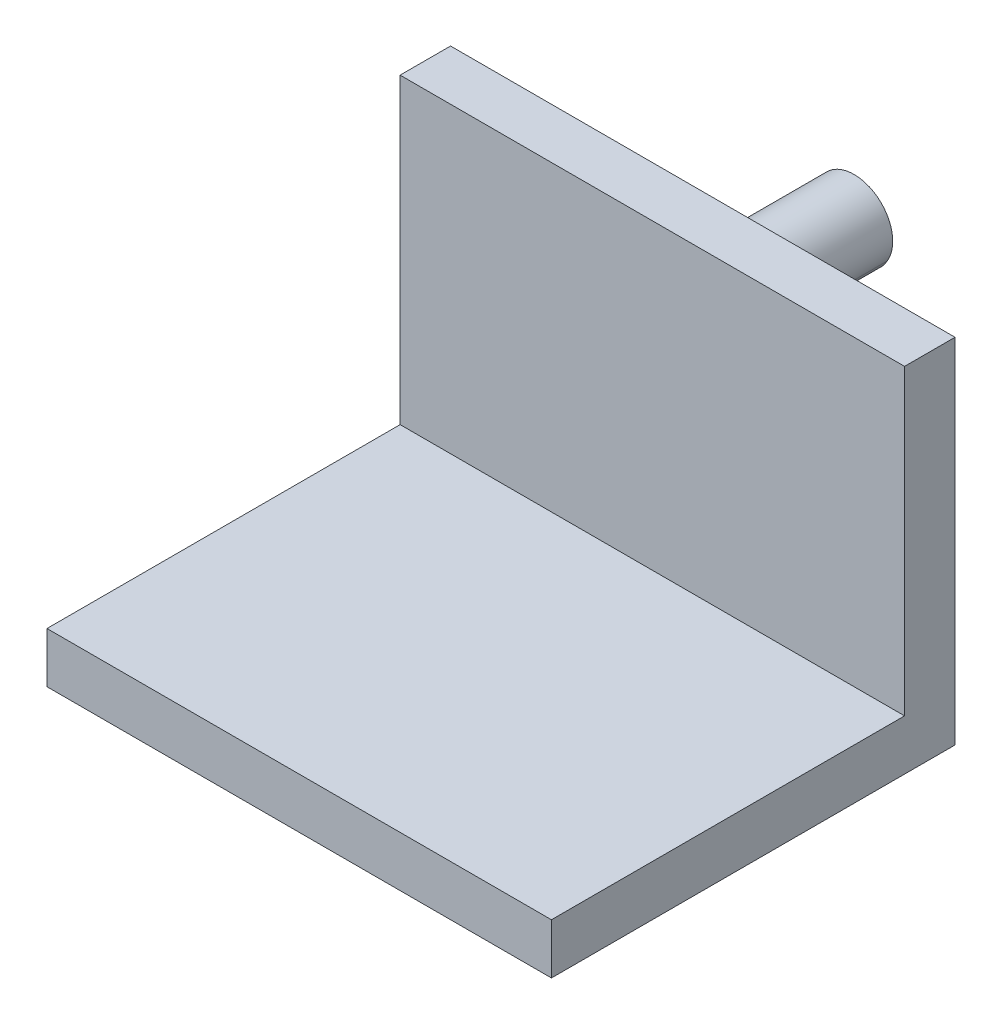
SolidWorks part; units mm, degrees
ref_plane "Front Plane" through (0, 0, 0) normal (0, 0, 1) x (1, 0, 0)
ref_plane "Top Plane" through (0, 0, 0) normal (0, 1, 0) x (1, 0, 0)
ref_plane "Right Plane" through (0, 0, 0) normal (1, 0, 0) x (0, 0, -1)
sketch "Sketch1" plane through (0, 0, 0) normal (0, 0, 1) x (1, 0, 0)
  line L0 (-66.057, 0) -> (58.5523, 0) construction
  line L1 (0, 49.7601) -> (0, -50.0946) construction
  line L3 (50, 35) -> (-50, 35)
  line L4 (50, 35) -> (50, -35)
  line L5 (50, -35) -> (-50, -35)
  line L6 (-50, 35) -> (-50, -35)
  dimension "D1" = 100
  dimension "D2" = 70
extrude "Boss-Extrude1" add sketch "Sketch1" along normal blind 10
sketch "Sketch2" plane through (-50, 0, 0) normal (-1, 0, 0) x (0, 0, 1)
  line L0 (10, -25) -> (80, -25)
  line L1 (10, 35) -> (10, -35) construction
  line L2 (80, -25) -> (80, -35)
  line L3 (80, -35) -> (10, -35)
  line L4 (10, -35) -> (10, -25)
  dimension "D1" = 70
  dimension "D2" = 10
extrude "Boss-Extrude3" add sketch "Sketch2" against normal blind 100
sketch "Sketch3" plane through (0, 0, 0) normal (0, 0, -1) x (-1, 0, 0)
  line L0 (0, 15) -> (-20.5318, 15) construction
  line L1 (0, 15) -> (0, 30.1359) construction
  line L2 (-50, 35) -> (-50, -35) construction
  line L3 (-50, -35) -> (50, -35) construction
  circle A0 centre (0, 15) radius 7.5
  dimension "D3" = 15
  dimension "D1" = 50
  dimension "D2" = 50
extrude "Boss-Extrude4" add sketch "Sketch3" along normal blind 30
sketch "Sketch4" plane through (0, 0, 0) normal (0, 0, -1) x (-1, 0, 0)
  line L0 (0, 15.3) -> (-20.8817, 15.3) construction
  line L1 (0, 15.3) -> (0, 30.8123) construction
  line L5 (-50, -35) -> (50, -35) construction
  line L6 (-50, 35) -> (-50, -35) construction
  circle A1 centre (0, 15.3) radius 7.65
  dimension "D1" = 15.3
  dimension "D2" = 50.3
  dimension "D3" = 50
extrude "Boss-Extrude5" add sketch "Sketch4" along normal blind 30
sketch "Sketch5" plane through (0, 0, 0) normal (0, 0, -1) x (-1, 0, 0)
  line L0 (0.3, 15) -> (-19.092, 15) construction
  line L1 (0.3, 15) -> (0.3, 33.1988) construction
  line L2 (-50, -35) -> (50, -35) construction
  line L3 (-50, 35) -> (-50, -35) construction
  circle A0 centre (0.3, 15) radius 7.65
  dimension "D3" = 15.3
  dimension "D1" = 50
  dimension "D2" = 50.3
extrude "Boss-Extrude6" add sketch "Sketch5" along normal blind 30
sketch "Sketch7" plane through (0, 0, 0) normal (0, 0, -1) x (-1, 0, 0)
  line L0 (0.3, 15.3) -> (-9.3925, 15.3) construction
  line L1 (0.3, 15.3) -> (0.3, 30.4848) construction
  line L2 (-50, -35) -> (50, -35) construction
  line L3 (-50, 35) -> (-50, -35) construction
  circle A0 centre (0.3, 15.3) radius 8
  dimension "D3" = 16
  dimension "D1" = 50.3
  dimension "D2" = 50.3
